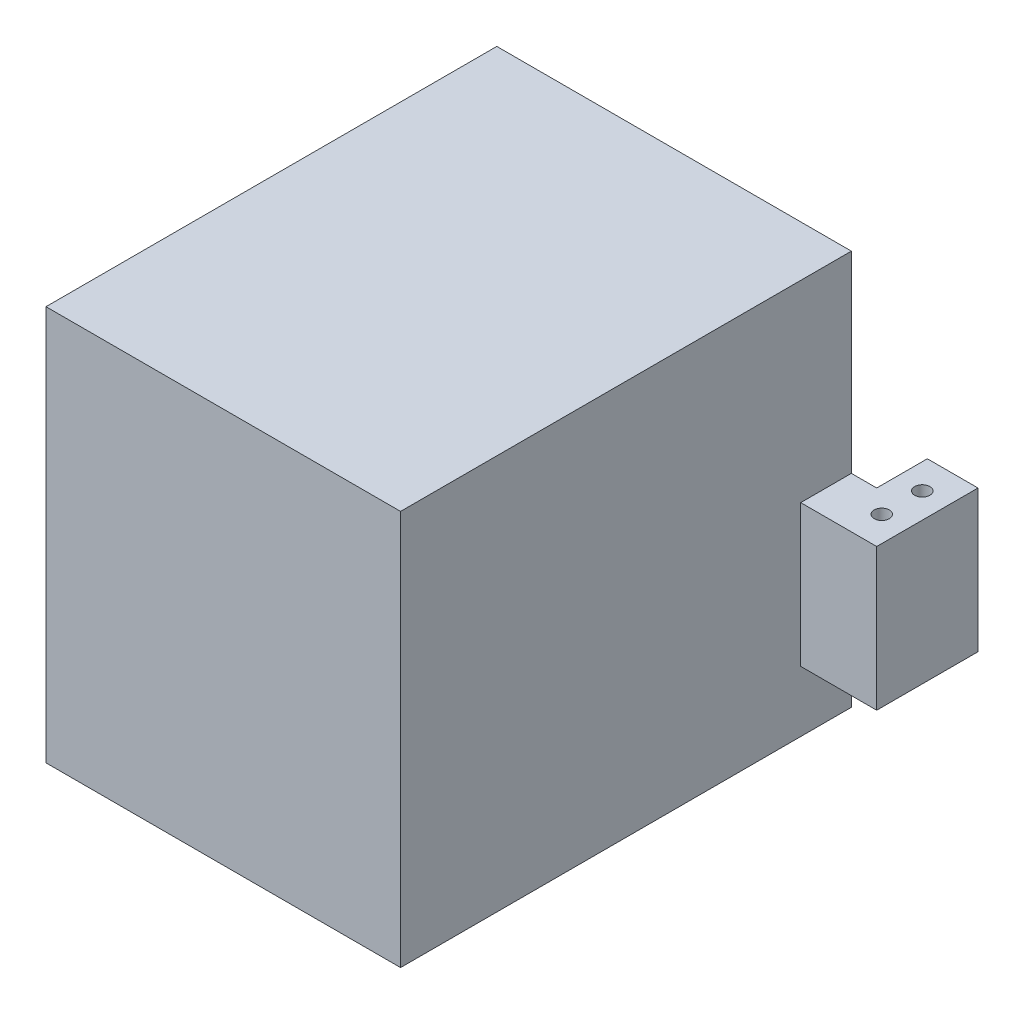
SolidWorks part; units mm, degrees
ref_plane "前视基准面" through (0, 0, 0) normal (0, 0, 1) x (1, 0, 0)
ref_plane "上视基准面" through (0, 0, 0) normal (0, 1, 0) x (1, 0, 0)
ref_plane "右视基准面" through (0, 0, 0) normal (1, 0, 0) x (0, 0, -1)
ref_plane "基准面4" through (0, 0, -10) normal (0, 0, -1) x (-1, 0, 0)
sketch "草图1" plane through (0, 0, -10) normal (0, 0, -1) x (-1, 0, 0)
  line L0 (50, 14) -> (-50, 14)
  line L1 (-50, 14) -> (-50, -14)
  line L2 (-50, -14) -> (50, -14)
  line L3 (50, -14) -> (50, 14)
extrude "凸台-拉伸1" add sketch "草图1" against normal blind 20
sketch "草图2" plane through (0, 14, 0) normal (0, 1, 0) x (-1, 0, 0)
  line L0 (-40, -10) -> (40, -10)
  line L1 (40, -10) -> (40, 0)
  line L2 (40, 0) -> (-40, 0)
  line L3 (-40, 0) -> (-40, -10)
extrude "切除-拉伸1" cut sketch "草图2" against normal through all
sketch "草图3" plane through (0, 14, 0) normal (0, 1, 0) x (-1, 0, 0)
  line L0 (-35, 10) -> (35, 10)
  line L1 (35, 10) -> (35, 0)
  line L2 (35, 0) -> (-35, 0)
  line L3 (-35, 0) -> (-35, 10)
extrude "凸台-拉伸2" add sketch "草图3" along normal blind 25
sketch "草图4" plane through (0, -14, 0) normal (0, -1, 0) x (1, 0, 0)
  line L0 (-35, 10) -> (35, 10)
  line L1 (35, 10) -> (35, 0)
  line L2 (35, 0) -> (-35, 0)
  line L3 (-35, 0) -> (-35, 10)
extrude "凸台-拉伸3" add sketch "草图4" along normal blind 12
hole_wizard "Ø3.0 (3) 直径孔1" positions "草图8" profile "草图7" hole size "Ø3.0" standard "ANSI Metric" end condition through all
sketch "草图8" plane through (0, 14, 0) normal (0, 1, 0) x (1, 0, 0)
  point P0 (-45, -4)
  point P1 (-45, 4)
sketch "草图7" plane through (-45, 14, 4) normal (1, 0, 0) x (0, 0, 1)
  line L0 (0, 0) -> (0, 40)
  line L1 (0, 40) -> (1.5, 40)
  line L2 (1.5, 40) -> (1.5, 0)
  line L5 (1.5, 0) -> (0, 0)
  line L11 (0, -6.35) -> (0, 107.95) construction
  dimension "通孔孔直径" = 3
  dimension "通孔孔深度" = 40
hole_wizard "Ø3.0 (3) 直径孔2" positions "草图10" profile "草图9" hole size "Ø3.0" standard "ANSI Metric" end condition through all
sketch "草图10" plane through (0, -14, 0) normal (0, -1, 0) x (-1, 0, 0)
  point P0 (-45, 4)
  point P1 (-45, -4)
sketch "草图9" plane through (45, -14, -4) normal (1, 0, 0) x (0, 0, -1)
  line L0 (0, 0) -> (0, 53)
  line L1 (0, 53) -> (1.5, 53)
  line L2 (1.5, 53) -> (1.5, 0)
  line L5 (1.5, 0) -> (0, 0)
  line L11 (0, -6.35) -> (0, 107.95) construction
  dimension "通孔孔直径" = 3
  dimension "通孔孔深度" = 53
sketch "草图13" plane through (0, 0, 0) normal (0, 0, -1) x (-1, 0, 0)
  line L0 (-35, 39) -> (35, 39)
  line L1 (35, 39) -> (35, 44)
  line L2 (35, 44) -> (-35, 44)
  line L3 (-35, 44) -> (-35, 39)
  dimension "D1" = 5
extrude "凸台-拉伸4" add sketch "草图13" against normal blind 10
sketch "草图15" plane through (0, 0, 0) normal (0, 0, -1) x (-1, 0, 0)
  line L0 (0, -26) -> (30, -26)
  line L1 (35, -26) -> (-35, -26) construction
  line L2 (30, -26) -> (30, 39)
  line L4 (0, -26) -> (-30, -26)
  line L5 (30, 39) -> (-30, 39)
  line L6 (-30, -26) -> (-30, 39)
  dimension "D1" = 30
  dimension "D2" = 30
extrude "切除-拉伸3" cut sketch "草图15" against normal blind 10
sketch "草图16" plane through (0, 0, 10) normal (0, 0, 1) x (1, 0, 0)
  line L0 (-35, -26) -> (-35, 44)
  line L1 (-35, 44) -> (35, 44)
  line L2 (35, 44) -> (35, -26)
  line L3 (35, -26) -> (30, -26)
  line L4 (30, -26) -> (30, 39)
  line L5 (30, 39) -> (-30, 39)
  line L6 (-30, 39) -> (-30, -26)
  line L7 (-30, -26) -> (-35, -26)
extrude "凸台-拉伸5" add sketch "草图16" along normal blind 74
sketch "草图17" plane through (0, 44, 0) normal (0, 1, 0) x (1, 0, 0)
  line L0 (-35, -84) -> (-35, -89)
  line L1 (-35, -84) -> (35, -84)
  line L2 (35, -84) -> (-35, -84) construction
  line L3 (35, -84) -> (35, -89)
  line L4 (35, -89) -> (-35, -89)
  dimension "D1" = 5
extrude "凸台-拉伸6" add sketch "草图17" against normal blind 70
sketch "草图18" plane through (0, 44, 0) normal (0, 1, 0) x (1, 0, 0)
  line L0 (-35, 0) -> (35, 0)
  line L1 (35, 0) -> (35, -89)
  line L2 (35, -89) -> (-35, -89)
  line L3 (-35, -89) -> (-35, 0)
extrude "凸台-拉伸7" add sketch "草图18" along normal blind 8
